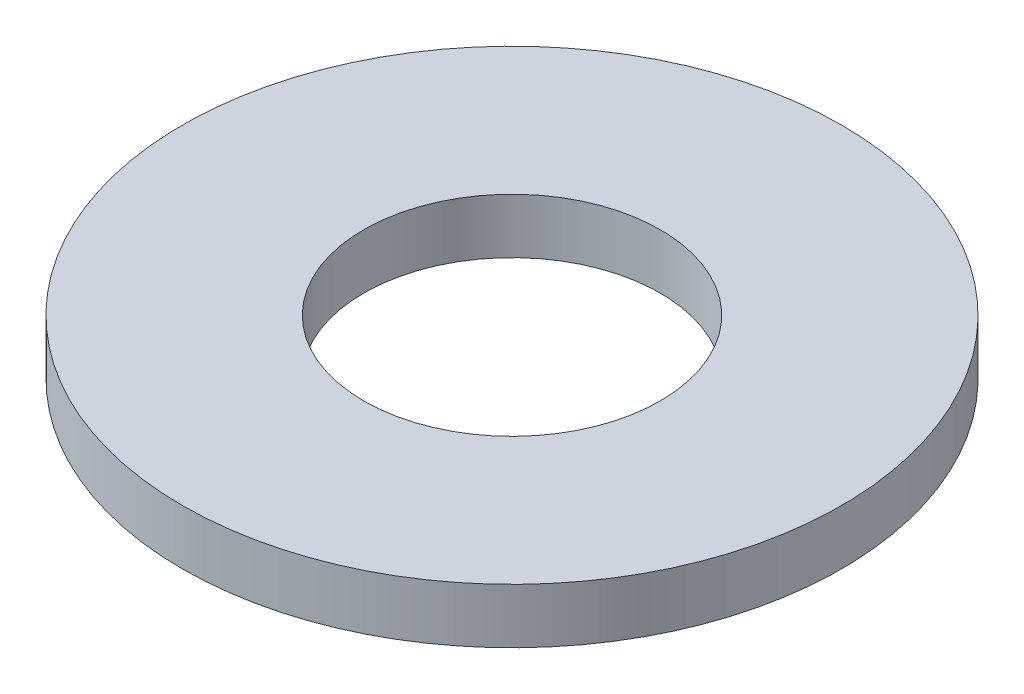
SolidWorks part; units mm, degrees
ref_plane "Alzado" through (0, 0, 0) normal (0, 0, 1) x (1, 0, 0)
ref_plane "Planta" through (0, 0, 0) normal (0, 1, 0) x (1, 0, 0)
ref_plane "Vista lateral" through (0, 0, 0) normal (1, 0, 0) x (0, 0, -1)
sketch "Croquis1" plane through (0, 0, 0) normal (0, 1, 0) x (1, 0, 0)
  circle A0 centre (0, 0) radius 1.35
  circle A1 centre (0, 0) radius 3
  dimension "D1" = 2.7
  dimension "D2" = 6
extrude "Saliente-Extruir1" add sketch "Croquis1" along normal blind 0.5
